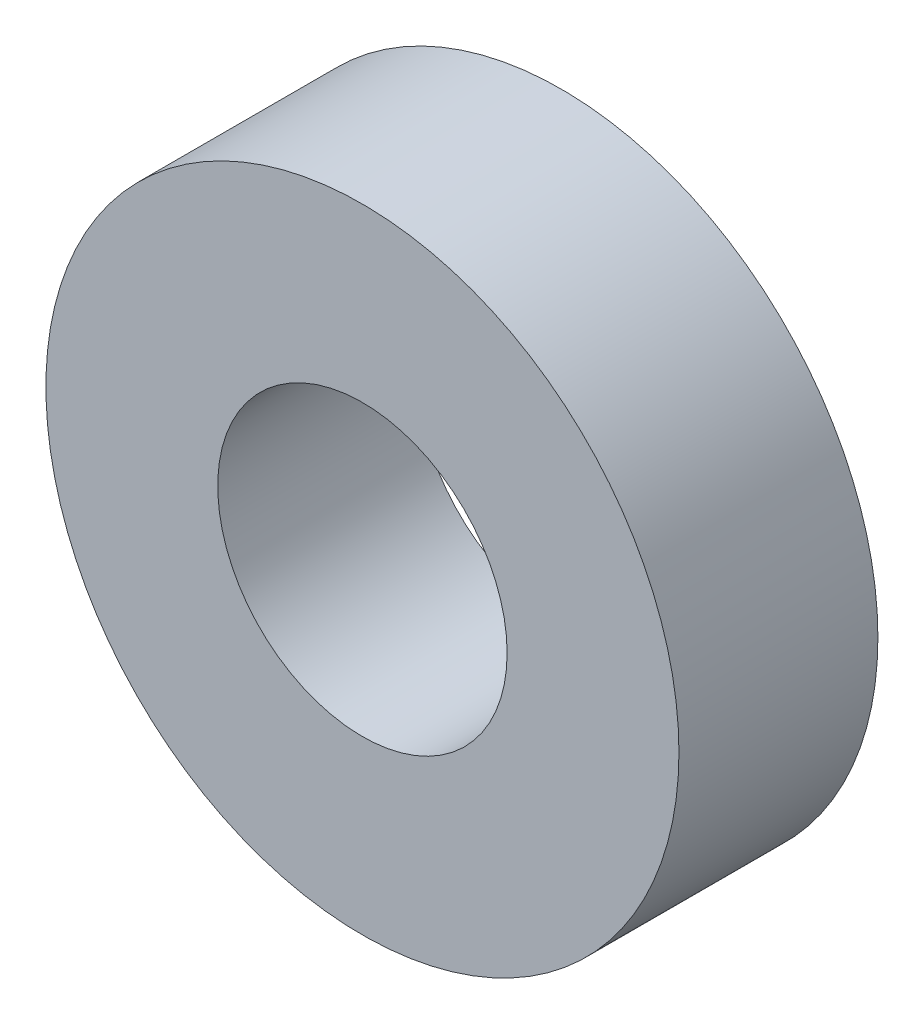
SolidWorks part; units mm, degrees
ref_plane "Front Plane" through (0, 0, 0) normal (0, 0, 1) x (1, 0, 0)
ref_plane "Top Plane" through (0, 0, 0) normal (0, 1, 0) x (1, 0, 0)
ref_plane "Right Plane" through (0, 0, 0) normal (1, 0, 0) x (0, 0, -1)
sketch "Sketch1" plane through (0, 0, 0) normal (0, 0, 1) x (1, 0, 0)
  circle A0 centre (0, 0) radius 8
  circle A1 centre (0, 0) radius 17.5
  dimension "D1" = 16
  dimension "D2" = 35
extrude "Boss-Extrude1" add sketch "Sketch1" along normal blind 11
